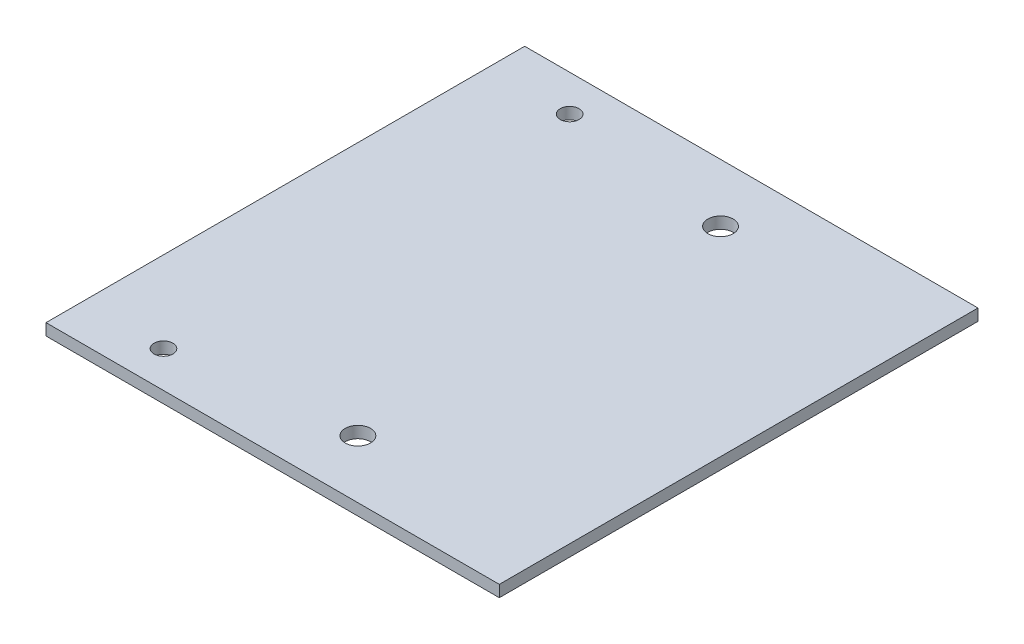
SolidWorks part; units mm, degrees
ref_plane "Front Plane" through (0, 0, 0) normal (0, 0, 1) x (1, 0, 0)
ref_plane "Top Plane" through (0, 0, 0) normal (0, 1, 0) x (1, 0, 0)
ref_plane "Right Plane" through (0, 0, 0) normal (1, 0, 0) x (0, 0, -1)
sketch "Sketch1" plane through (0, 0, 0) normal (0, 1, 0) x (1, 0, 0)
  line L1 (-31.25, -33) -> (31.25, -33)
  line L2 (-31.25, -33) -> (-31.25, 33)
  line L3 (-31.25, 33) -> (31.25, 33)
  line L4 (31.25, -33) -> (31.25, 33)
  line L5 (-31.25, -33) -> (31.25, 33) construction
  line L6 (-31.25, 33) -> (31.25, -33) construction
  point P0 (0, 0)
  dimension "D1" = 62.5
  dimension "D2" = 66
extrude "Boss-Extrude1" add sketch "Sketch1" along normal blind 1.6
sketch "Sketch2" plane through (0, 1.6, 0) normal (0, 1, 0) x (1, 0, 0)
  line L1 (-31.25, 33) -> (-31.25, -33) construction
  circle A0 centre (-20.052, 28) radius 1.3
  circle A1 centre (-20.052, -28) radius 1.3
  dimension "D1" = 11.198
  dimension "D2" = 56
  dimension "D4" = 2.6
  dimension "D5" = 2.6
  dimension "D3" = 28
extrude "Cut-Extrude1" cut sketch "Sketch2" against normal blind 10
sketch "Sketch3" plane through (0, 1.6, 0) normal (0, 1, 0) x (1, 0, 0)
  line L0 (-31.25, -33) -> (31.25, -33) construction
  line L1 (31.25, 33) -> (-31.25, 33) construction
  line L2 (31.25, -33) -> (31.25, 33) construction
  circle A0 centre (3.75, 25) radius 1.75
  circle A1 centre (3.75, -25) radius 1.75
  dimension "D1" = 3.5
  dimension "D2" = 3.5
  dimension "D3" = 8
  dimension "D4" = 8
  dimension "D5" = 27.5
  dimension "D6" = 27.5
extrude "Cut-Extrude2" cut sketch "Sketch3" against normal up to next
